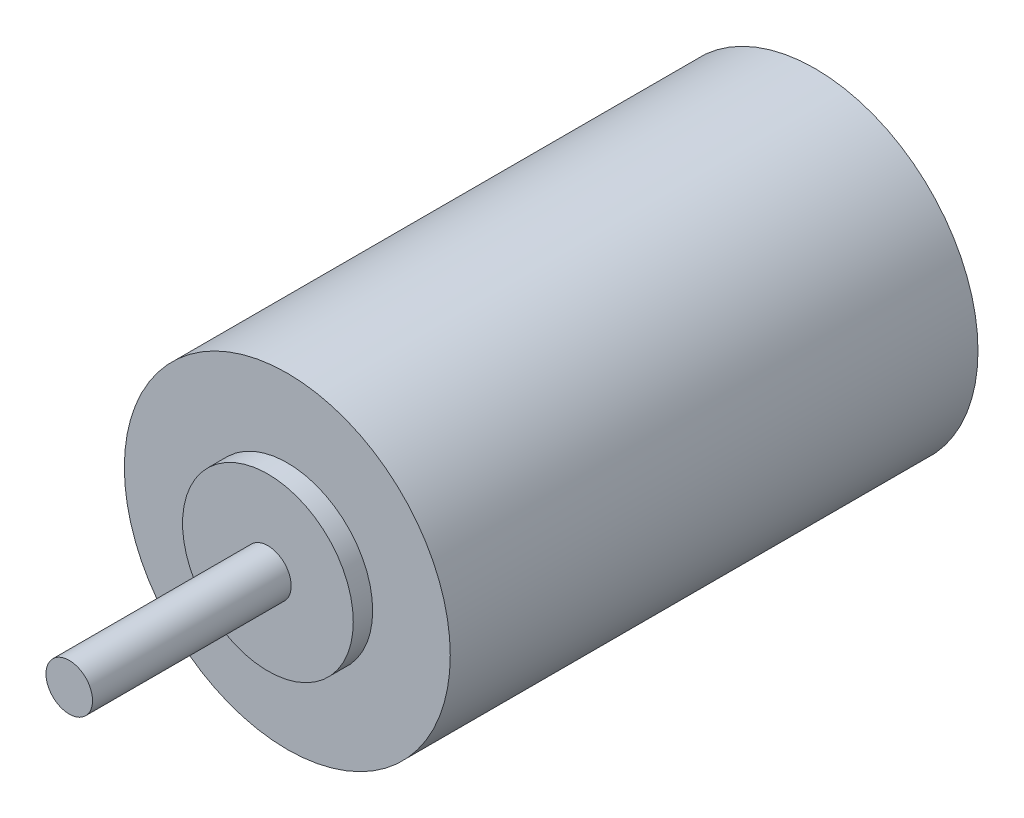
SolidWorks part; units mm, degrees
ref_plane "Alzado" through (0, 0, 0) normal (0, 0, 1) x (1, 0, 0)
ref_plane "Planta" through (0, 0, 0) normal (0, 1, 0) x (1, 0, 0)
ref_plane "Vista lateral" through (0, 0, 0) normal (1, 0, 0) x (0, 0, -1)
sketch "Croquis1" plane through (0, 0, 0) normal (0, 0, 1) x (1, 0, 0)
  circle A0 centre (0, 0) radius 21
  dimension "D1" = 42
extrude "Saliente-Extruir1" add sketch "Croquis1" along normal blind 68
sketch "Croquis2" plane through (0, 0, 68) normal (0, 0, 1) x (1, 0, 0)
  circle A0 centre (0, 0) radius 11
  dimension "D1" = 22
extrude "Saliente-Extruir2" add sketch "Croquis2" along normal blind 2.5
sketch "Croquis3" plane through (0, 0, 70.5) normal (0, 0, 1) x (1, 0, 0)
  circle A0 centre (0, 0) radius 3
  dimension "D1" = 6
extrude "Saliente-Extruir3" add sketch "Croquis3" along normal blind 25.6
